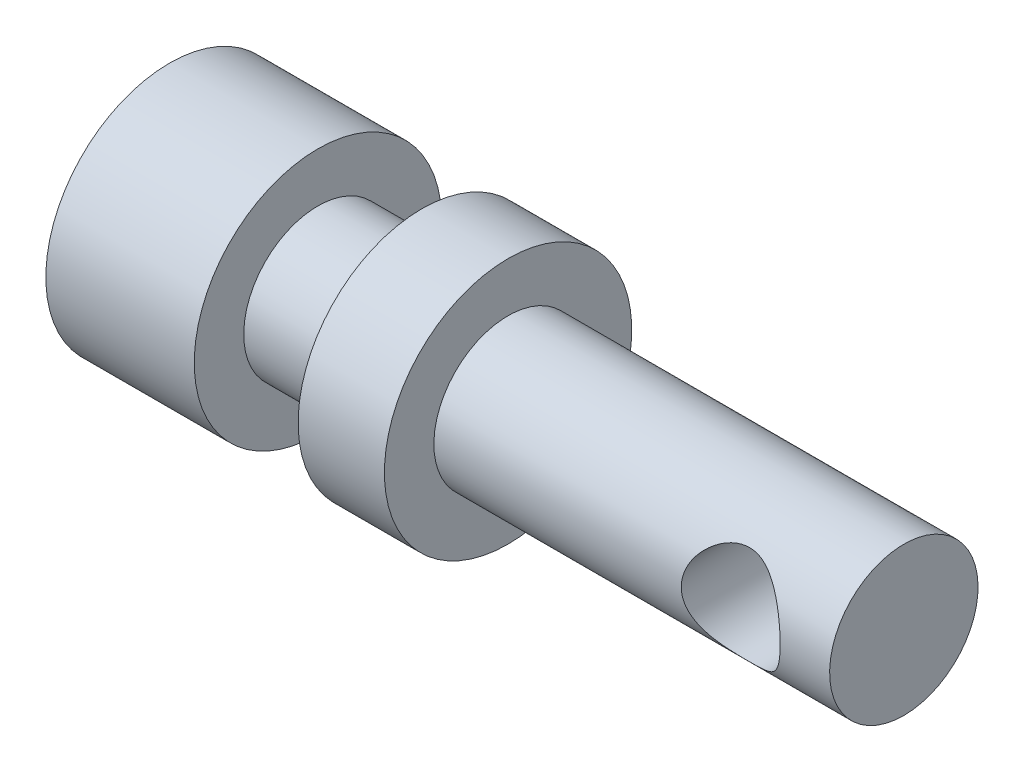
SolidWorks part; units mm, degrees
material "Brass"
ref_plane "Front Plane" through (0, 0, 0) normal (0, 0, 1) x (1, 0, 0)
ref_plane "Top Plane" through (0, 0, 0) normal (0, 1, 0) x (1, 0, 0)
ref_plane "Right Plane" through (0, 0, 0) normal (1, 0, 0) x (0, 0, -1)
other "Center of Mass"
sketch "Sketch1" plane through (0, 0, 0) normal (0, 0, 1) x (1, 0, 0)
  line L0 (0, 2.5) -> (0, 0)
  line L1 (0, 0) -> (8.8439, 0)
  line L3 (6.8439, 2.5) -> (5.1, 2.5)
  line L4 (5.1, 2.5) -> (5.1, 1.5)
  line L5 (5.1, 1.5) -> (3, 1.5)
  line L6 (3, 1.5) -> (3, 2.5)
  line L7 (3, 2.5) -> (0, 2.5)
  line L8 (6.8439, 2.5) -> (6.8439, 1.5)
  line L9 (6.8439, 1.5) -> (14.8439, 1.5)
  line L12 (14.8439, 1.5) -> (14.8439, 0)
  line L13 (14.8439, 0) -> (8.8439, 0)
  point P5 (8.8439, 1.5)
  point P11 (14.6533, 1.5)
  point P15 (0, 0)
  point P16 (14.7441, 3.5681)
  point P17 (14.7584, 1.5)
  dimension "D1" = 2.1
  dimension "D2" = 2.5
  dimension "D3" = 3
  dimension "D4" = 8
  dimension "D5" = 1.5
  dimension "D6" = 6
revolve "Revolve1" add sketch "Sketch1" angle 360 about L1
ref_point "Point1"
sketch "Sketch2" plane through (0, 0, 0) normal (0, 0, 1) x (1, 0, 0)
  line L0 (14.8439, -1.5) -> (14.8439, 1.5) construction
  circle A0 centre (12.8439, 0) radius 1
  dimension "D1" = 2
  dimension "D2" = 2
extrude "Cut-Extrude1" cut sketch "Sketch2" against normal through all both and the other way through all
